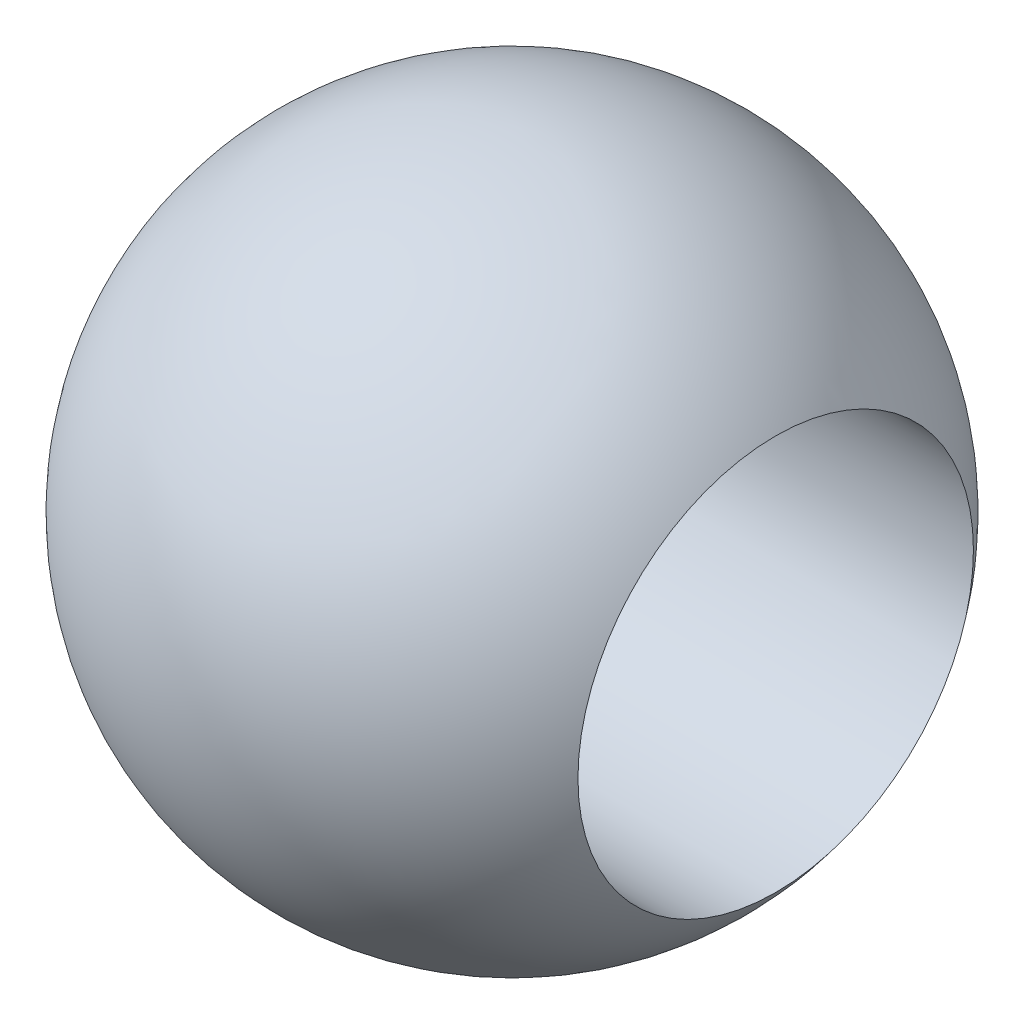
SolidWorks part; units mm, degrees
material "AISI 316 Stainless Steel Sheet (SS)"
ref_plane "Front Plane" through (0, 0, 0) normal (0, 0, 1) x (1, 0, 0)
ref_plane "Top Plane" through (0, 0, 0) normal (0, 1, 0) x (1, 0, 0)
ref_plane "Right Plane" through (0, 0, 0) normal (1, 0, 0) x (0, 0, -1)
sketch "Sketch1" plane through (0, 0, 0) normal (0, 0, 1) x (1, 0, 0)
  line L0 (0, 0) -> (0, 9.525) construction
  line L1 (-7.2673, 0) -> (7.2673, 0) construction
  line L2 (-7.62, 5.715) -> (7.62, 5.715)
  arc A0 (-7.62, 5.715) -> (7.62, 5.715) centre (0, 0) cw
  circle A1 centre (0, 0) radius 5.715 construction
  point P6 (0, 0)
  dimension "D2" = 9.525
  dimension "D3" = 11.43
  dimension "D1" = 11.43
revolve "Revolve1" add sketch "Sketch1" angle 360 about L1
sketch "Sketch2" plane through (0, 0, 0) normal (0, 1, 0) x (1, 0, 0)
  line L0 (0, 0) -> (0, 10.16) construction
  line L1 (-1.27, 10.16) -> (1.27, 10.16)
  line L2 (-1.27, 10.16) -> (-1.27, 8.89)
  line L3 (-1.27, 8.89) -> (1.27, 8.89)
  line L4 (1.27, 10.16) -> (1.27, 8.89)
  point P4 (1.0855, 8.7773)
  dimension "D1" = 2.54
  dimension "D2" = 8.89
  dimension "D3" = 1.27
extrude "Cut-Extrude1" cut sketch "Sketch2" against normal through all both and the other way through all
